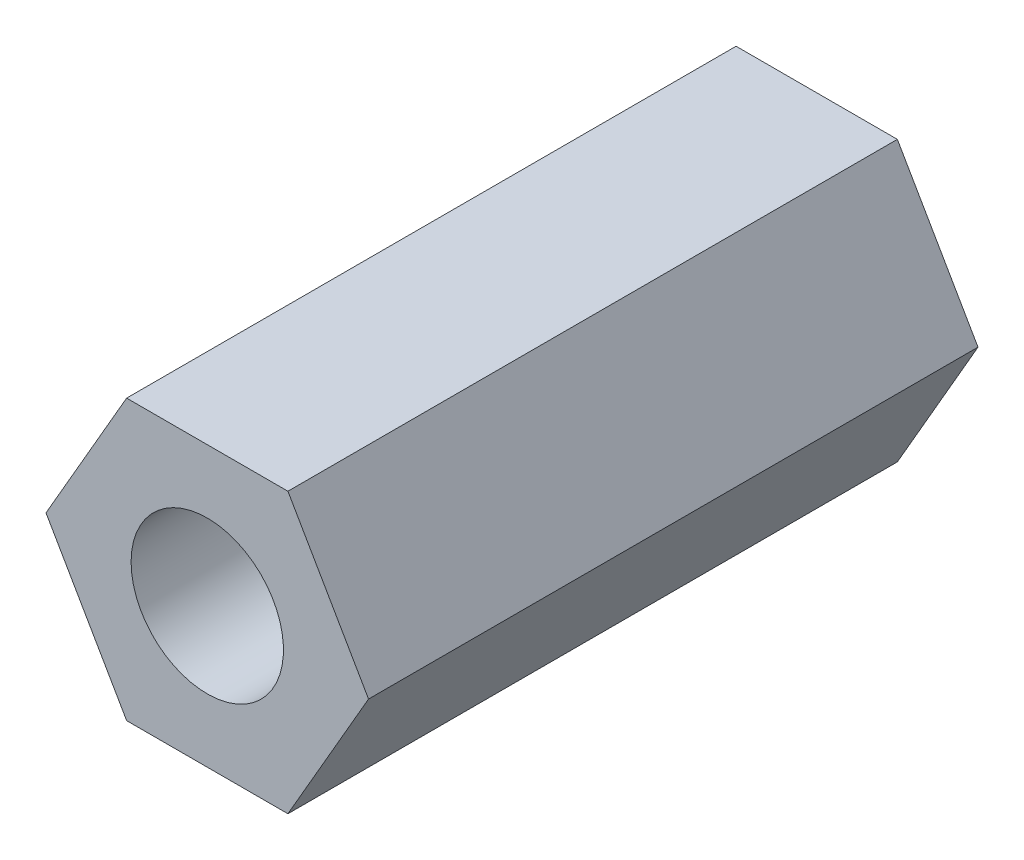
SolidWorks part; units mm, degrees
ref_plane "Face" through (0, 0, 0) normal (0, 0, 1) x (1, 0, 0)
ref_plane "Dessus" through (0, 0, 0) normal (0, 1, 0) x (1, 0, 0)
ref_plane "Droite" through (0, 0, 0) normal (1, 0, 0) x (0, 0, -1)
sketch "Esquisse1" plane through (0, 0, 0) normal (0, 0, 1) x (1, 0, 0)
  line L1 (1.5877, 2.75) -> (-1.5877, 2.75)
  line L2 (-1.5877, 2.75) -> (-3.1754, 0)
  line L3 (-3.1754, 0) -> (-1.5877, -2.75)
  line L4 (-1.5877, -2.75) -> (1.5877, -2.75)
  line L5 (1.5877, -2.75) -> (3.1754, 0)
  line L6 (3.1754, 0) -> (1.5877, 2.75)
  circle A0 centre (0, 0) radius 2.75 construction
  dimension "D1" = 5.5
extrude "Base-Extrusion" add sketch "Esquisse1" along normal blind 12
sketch "Esquisse3" plane through (0, 0, 0) normal (0, 0, -1) x (-1, 0, 0)
  circle A0 centre (0, 0) radius 1.5
extrude "Enlèv. mat.-Extru.1" cut sketch "Esquisse3" against normal through all
